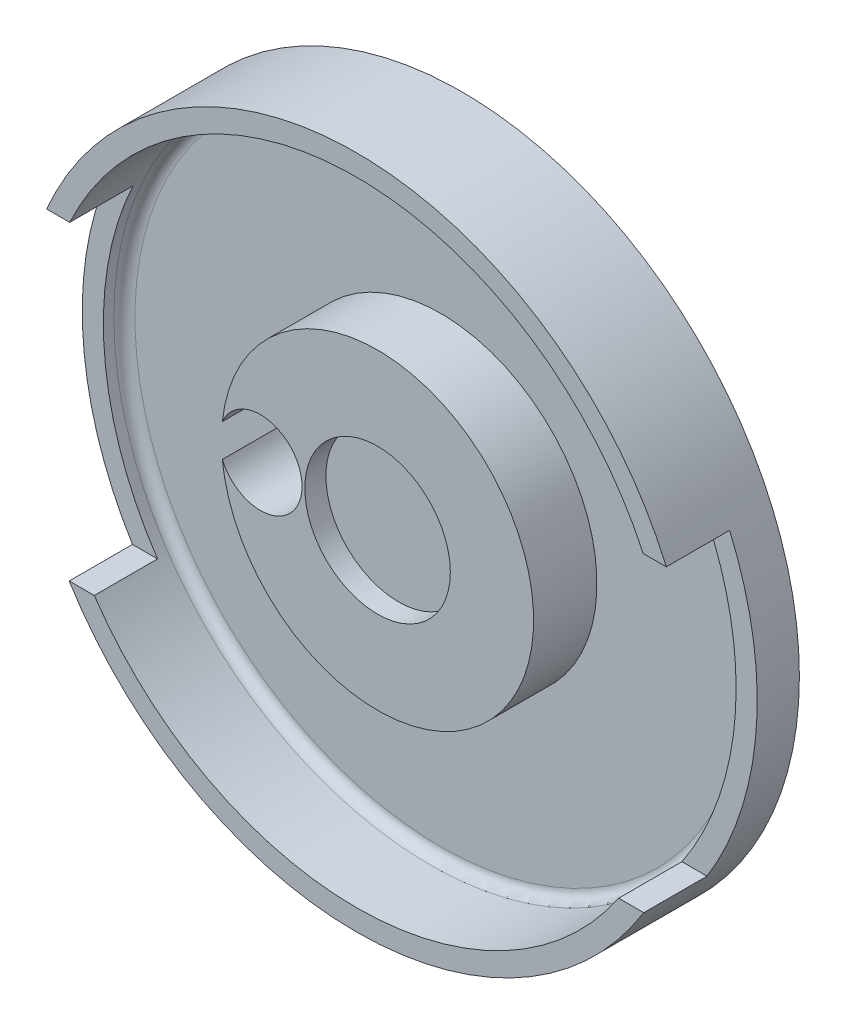
SolidWorks part; units mm, degrees
ref_plane "Front Plane" through (0, 0, 0) normal (0, 0, 1) x (1, 0, 0)
ref_plane "Top Plane" through (0, 0, 0) normal (0, 1, 0) x (1, 0, 0)
ref_plane "Right Plane" through (0, 0, 0) normal (1, 0, 0) x (0, 0, -1)
sketch "Sketch1" plane through (0, 0, 0) normal (0, 0, 1) x (1, 0, 0)
  circle A0 centre (0, 0) radius 16
extrude "Boss-Extrude1" add sketch "Sketch1" along normal blind 5
sketch "Sketch3" plane through (0, 0, 5) normal (0, 0, 1) x (1, 0, 0)
  circle A0 centre (0, 0) radius 15
extrude "Cut-Extrude1" cut sketch "Sketch3" against normal blind 4 contours A0
fillet "Fillet1" radius 0.5 1 edges at (15, 0, 1)
ref_plane "Plane4" through (0, 0, 13) normal (0, 0, 1) x (1, 0, 0)
sketch "Sketch7" plane through (0, 0, 13) normal (0, 0, 1) x (1, 0, 0)
  line L1 (-17.0905, 6.3393) -> (-11.822, 6.3393)
  line L2 (-17.0905, 6.3393) -> (-17.0905, -8.3958)
  line L3 (-17.0905, -8.3958) -> (-11.822, -8.3958)
  line L4 (-11.822, 6.3393) -> (-11.822, -8.3958)
  circle A0 centre (0, 0) radius 14.5 construction
extrude "Cut-Extrude2" cut sketch "Sketch7" against normal blind 11 contours L4 L3 L2 L1
mirror "Mirror1" about plane through (0, 0, 0) normal (1, 0, 0) of "Cut-Extrude2"
sketch "Sketch8" plane through (0, 0, 1) normal (0, 0, 1) x (1, 0, 0)
  circle A0 centre (0, 0) radius 7.4
extrude "Boss-Extrude2" add sketch "Sketch8" along normal blind 3 contours A0
sketch "Sketch9" plane through (0, 0, 4) normal (0, 0, 1) x (1, 0, 0)
  circle A0 centre (0, 0) radius 3.45
extrude "Cut-Extrude3" cut sketch "Sketch9" against normal blind 1
sketch "Sketch5" plane through (0, 0, 1) normal (0, 0, 1) x (1, 0, 0)
  circle A0 centre (0, 0) radius 1.275
  dimension "D1" = 2.55
sketch "Sketch6" plane through (0, 0, 13) normal (0, 0, 1) x (1, 0, 0)
  circle A0 centre (0, 0) radius 1.3
sketch "Sketch11" plane through (0, 0, 4) normal (0, 0, 1) x (1, 0, 0)
  circle A0 centre (-5.5497, 0) radius 1.9694
extrude "Cut-Extrude4" cut sketch "Sketch11" against normal blind 10
